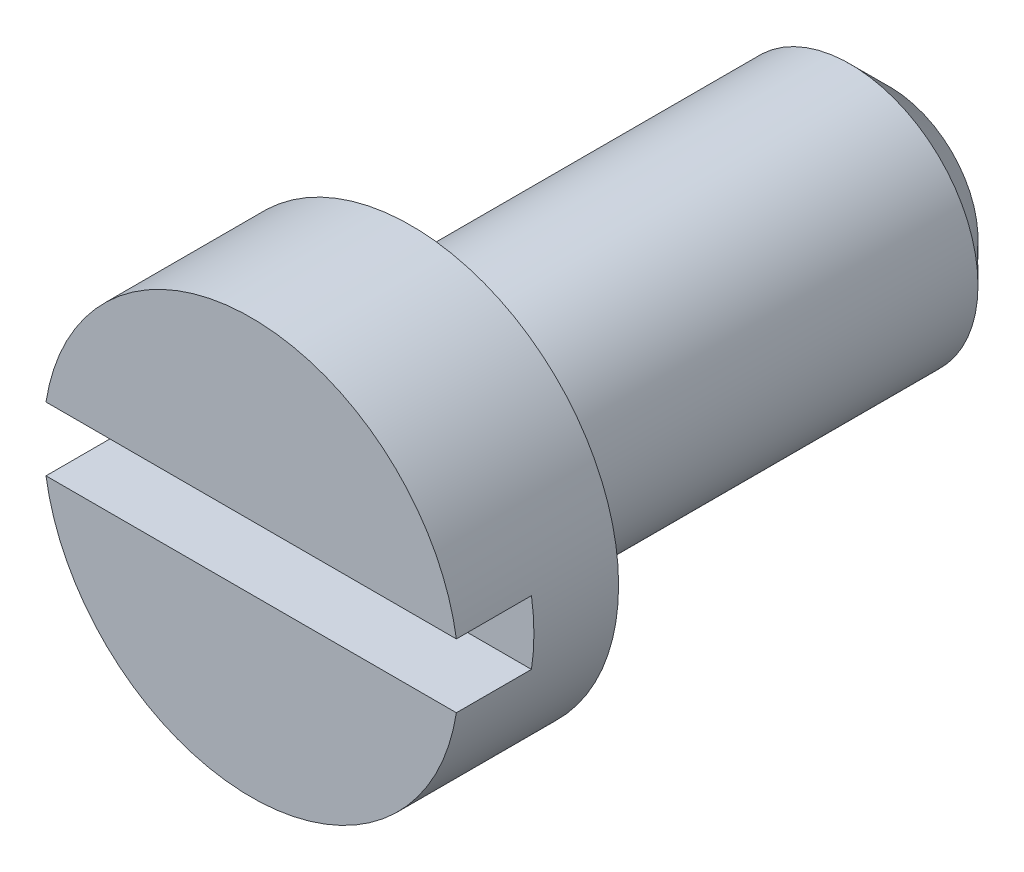
SolidWorks part; units mm, degrees
ref_plane "Спереди" through (0, 0, 0) normal (0, 0, 1) x (1, 0, 0)
ref_plane "Сверху" through (0, 0, 0) normal (0, 1, 0) x (1, 0, 0)
ref_plane "Справа" through (0, 0, 0) normal (1, 0, 0) x (0, 0, -1)
sketch "Эскиз12" plane through (0, 0, 0) normal (0, 0, 1) x (1, 0, 0)
  circle A0 centre (0, 0) radius 6.5
extrude "Вытянуть3" add sketch "Эскиз12" along normal blind 5
sketch "Эскиз13" plane through (0, 0, 0) normal (0, 0, -1) x (-1, 0, 0)
  circle A0 centre (0, 0) radius 4
extrude "Вытянуть4" add sketch "Эскиз13" along normal blind 15
sketch "Эскиз14" plane through (0, 0, 5) normal (0, 0, 1) x (1, 0, 0)
  line L0 (-6.5, 0) -> (6.5, 0) construction
  circle A0 centre (0, 0) radius 6.5 construction
sketch "Эскиз20" plane through (0, 0, 5) normal (0, 0, 1) x (1, 0, 0)
  line L0 (-6.5, 0) -> (6.5, 0) construction
  line L1 (-6.8318, 1) -> (6.854, 1)
  line L2 (-6.8318, 1) -> (-6.8318, -1)
  line L3 (-6.8318, -1) -> (6.854, -1)
  line L4 (6.854, 1) -> (6.854, -1)
  dimension "D1" = 1
  dimension "D2" = 1
extrude "Вырез-Вытянуть8" cut sketch "Эскиз20" against normal blind 2.35
chamfer "Фаска1" distance 1.25 angle 45 1 edges at (-4, 0, -15)
